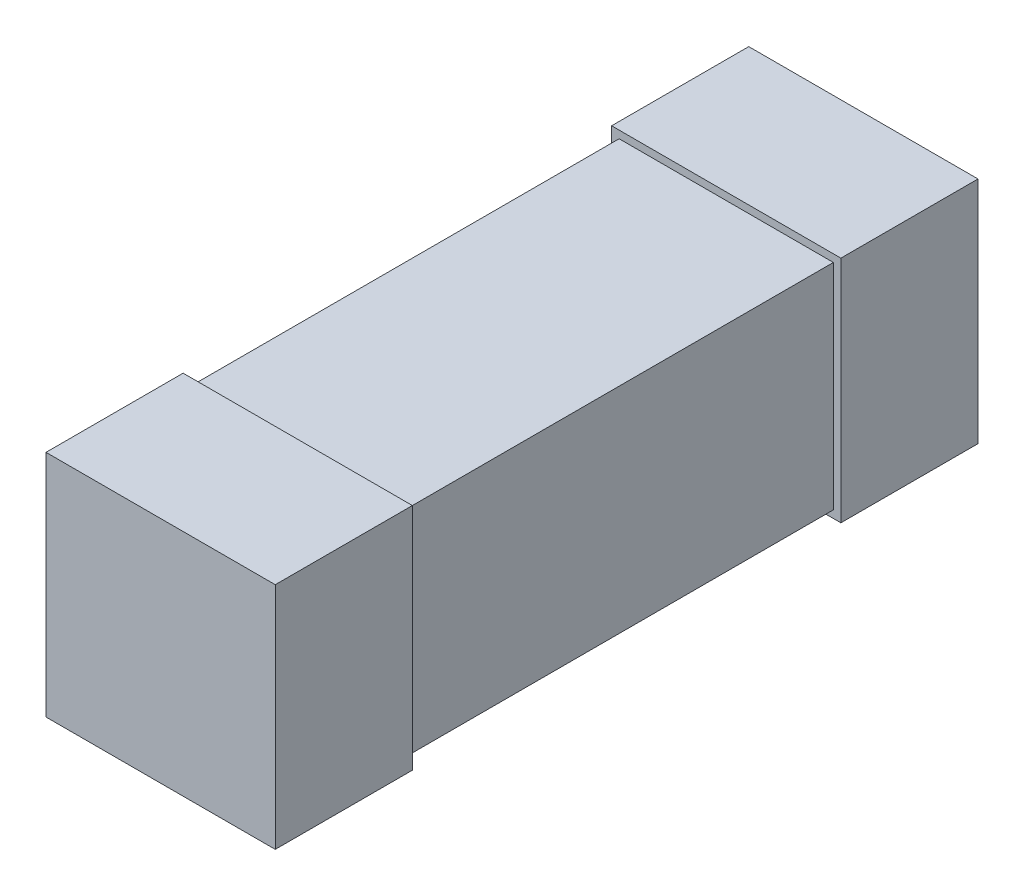
SolidWorks part; units mm, degrees
ref_plane "Front Plane" through (0, 0, 0) normal (0, 0, 1) x (1, 0, 0)
ref_plane "Top Plane" through (0, 0, 0) normal (0, 1, 0) x (1, 0, 0)
ref_plane "Right Plane" through (0, 0, 0) normal (1, 0, 0) x (0, 0, -1)
sketch "Sketch1" plane through (0, 0, 0) normal (0, 0, 1) x (1, 0, 0)
  line L1 (0, 0) -> (-5.35, 0)
  line L2 (0, 0) -> (0, 5.35)
  line L3 (0, 5.35) -> (-5.35, 5.35)
  line L4 (-5.35, 0) -> (-5.35, 5.35)
  dimension "D1" = 5.35
  dimension "D2" = 5.35
extrude "Boss-Extrude1" add sketch "Sketch1" along normal blind 3.2
sketch "Sketch2" plane through (0, 0, 3.2) normal (0, 0, 1) x (1, 0, 0)
  line L0 (-2.675, 5.35) -> (-2.675, 0) construction
  line L1 (0, 5.35) -> (-5.35, 5.35) construction
  line L2 (-5.35, 0) -> (0, 0) construction
  line L4 (-0.175, 5.175) -> (-5.175, 5.175)
  line L5 (-0.175, 5.175) -> (-0.175, 0.175)
  line L6 (-0.175, 0.175) -> (-5.175, 0.175)
  line L7 (-5.175, 5.175) -> (-5.175, 0.175)
  line L8 (-0.175, 5.175) -> (-5.175, 0.175) construction
  line L9 (-0.175, 0.175) -> (-5.175, 5.175) construction
  point P6 (-2.675, 2.675)
  dimension "D1" = 5
  dimension "D2" = 5
extrude "Boss-Extrude2" add sketch "Sketch2" along normal blind 10
sketch "Sketch3" plane through (0, 0, 13.2) normal (0, 0, 1) x (1, 0, 0)
  line L0 (-2.675, 5.175) -> (-2.675, 0.175) construction
  line L1 (-0.175, 5.175) -> (-5.175, 5.175) construction
  line L2 (-5.175, 0.175) -> (-0.175, 0.175) construction
  line L4 (0, 5.35) -> (-5.35, 5.35)
  line L5 (0, 5.35) -> (0, 0)
  line L6 (0, 0) -> (-5.35, 0)
  line L7 (-5.35, 5.35) -> (-5.35, 0)
  line L8 (0, 5.35) -> (-5.35, 0) construction
  line L9 (0, 0) -> (-5.35, 5.35) construction
  point P6 (-2.675, 2.675)
  dimension "D1" = 5.35
  dimension "D2" = 5.35
extrude "Boss-Extrude3" add sketch "Sketch3" along normal blind 3.2
